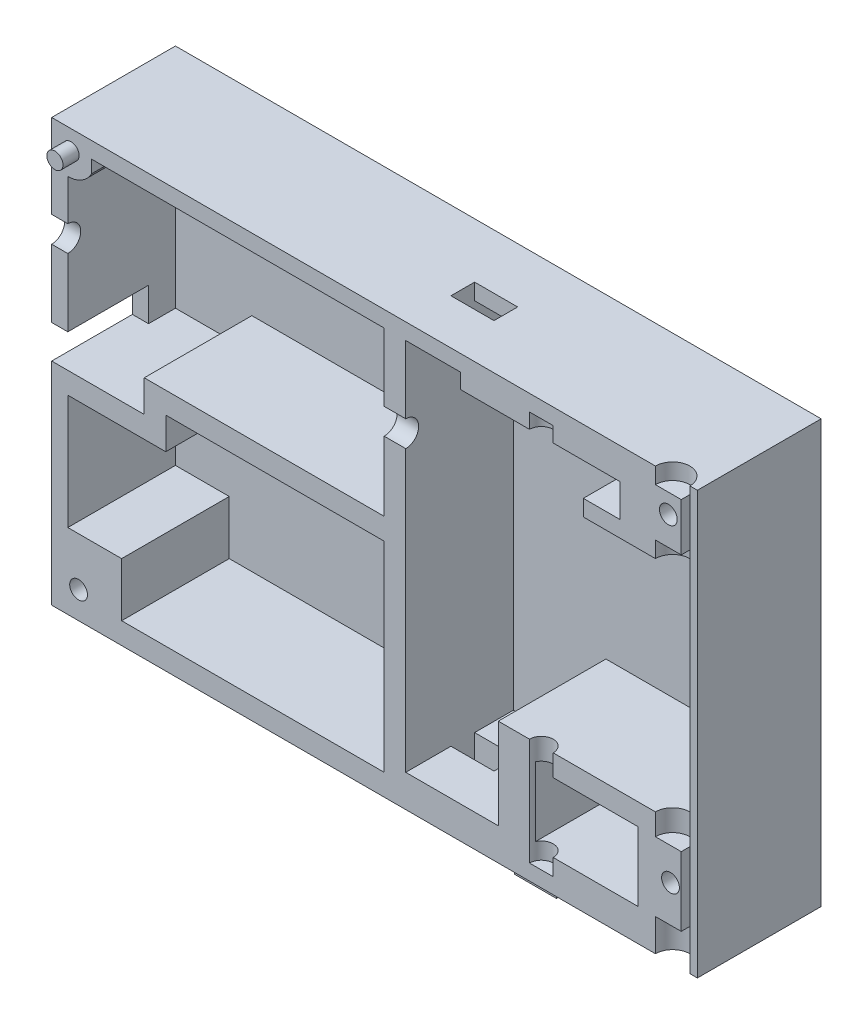
SolidWorks part; units mm, degrees
ref_plane "前视基准面" through (0, 0, 0) normal (0, 0, 1) x (1, 0, 0)
ref_plane "上视基准面" through (0, 0, 0) normal (0, 1, 0) x (1, 0, 0)
ref_plane "右视基准面" through (0, 0, 0) normal (1, 0, 0) x (0, 0, -1)
sketch "草图1" plane through (0, 0, 0) normal (0, 0, 1) x (1, 0, 0)
  line L1 (-30, 26) -> (30, 26)
  line L2 (-30, 26) -> (-30, -26)
  line L3 (-30, -26) -> (30, -26)
  line L4 (30, 26) -> (30, -26)
  line L5 (-30, 26) -> (30, -26) construction
  line L6 (-30, -26) -> (30, 26) construction
  point P0 (0, 0)
  dimension "D1" = 52
  dimension "D2" = 60
extrude "凸台-拉伸1" add sketch "草图1" along normal blind 11.5
shell "抽壳1" thickness 1.5
sketch "草图2" plane through (0, 0, 1.5) normal (0, 0, 1) x (1, 0, 0)
  line L0 (-21.4, 9.35) -> (0.9, 9.35)
  line L1 (-28.5, 24.5) -> (-28.5, -24.5) construction
  line L9 (28.5, -10.25) -> (14.5, -10.25)
  line L14 (0.9, -11.25) -> (0.9, 7.35)
  line L15 (0.9, 7.35) -> (-19.4, 7.35)
  line L17 (0.9, 24.5) -> (0.9, 9.35)
  line L18 (28.5, 24.5) -> (-28.5, 24.5) construction
  line L20 (0.9, 24.5) -> (2.9, 24.5)
  line L21 (8, 24.5) -> (8, 23.1)
  line L22 (8, 23.1) -> (23, 23.1)
  line L23 (23, 23.1) -> (23, 24.5)
  line L24 (23, 24.5) -> (8, 24.5)
  line L28 (2.9, 24.5) -> (2.9, -10.25)
  line L29 (0.8, 14) -> (0.8, 20) construction
  line L30 (-1.2, 9.5) -> (-21.7, 9.5) construction
  line L31 (-21.4, 9.35) -> (-21.4, 6.4)
  line L32 (-21.4, 6.4) -> (-28.5, 6.4)
  line L34 (-28.5, 4.4) -> (-19.4, 4.4)
  line L35 (-19.4, 4.4) -> (-19.4, 7.35)
  line L36 (-21.7, 6.5) -> (-27.2, 6.5) construction
  line L37 (-21.7, 6.5) -> (-21.7, 9.5) construction
  line L38 (15.5, 24.5) -> (15.5, 13.1928) construction
  line L39 (16.5, 24.5) -> (14.5, 24.5) construction
  line L41 (28.5, -13.25) -> (-4.1, -13.25)
  line L48 (19.4, 18.55) -> (28.5, 18.55)
  line L55 (11.5, -10.25) -> (2.9, -10.25)
  line L60 (-28.5, 4.4) -> (-28.5, 6.4)
  line L62 (28.5, -24.5) -> (28.5, 24.5) construction
  line L63 (28.5, 18.55) -> (28.5, 20.05)
  line L64 (28.5, 20.05) -> (19.4, 20.05)
  line L67 (19.4, 20.05) -> (19.4, 18.55)
  line L68 (28.5, -10.25) -> (28.5, -13.25)
  line L69 (11.5, -1.83) -> (28.5, -1.83)
  line L70 (28.5, -1.83) -> (28.5, -3.83)
  line L71 (28.5, -3.83) -> (14.5, -3.83)
  line L73 (0.9, -11.25) -> (-28.5, -11.25)
  line L74 (19.3656, -1.73) -> (20.5824, -1.73) construction
  line L75 (-28.5, -11.25) -> (-28.5, -13.25)
  line L76 (-28.5, -13.25) -> (-4.1, -13.25)
  line L77 (14.5, -3.83) -> (14.5, -10.25)
  line L79 (11.5, -10.25) -> (11.5, -1.83)
  dimension "D3" = 3
  dimension "D4" = 34.75
  dimension "D5" = 1.5
  dimension "D6" = 2
  dimension "D7" = 9.1
  dimension "D8" = 2
  dimension "D9" = 0.15
  dimension "D10" = 2
  dimension "D11" = 0.1
  dimension "D12" = 2
  dimension "D13" = 4.45
  dimension "D14" = 0.1
  dimension "D15" = 0.3
  dimension "D16" = 1.4
  dimension "D17" = 15
  dimension "D18" = 2
  dimension "D19" = 0.1
  dimension "D20" = 17
  dimension "D21" = 2
  dimension "D22" = 3
extrude "凸台-拉伸2" add sketch "草图2" along normal up to surface (10 mm away) up to face at (0, 0, 11.5)
sketch "草图3" plane through (0, -26, 0) normal (0, -1, 0) x (1, 0, 0)
  line L0 (2.9, 7.3) -> (6.9, 7.3)
  line L2 (6.9, 7.3) -> (6.9, 5.1)
  line L3 (6.9, 5.1) -> (2.9, 5.1)
  line L4 (2.9, 5.1) -> (2.9, 7.3)
  line L6 (2.9, 11.5) -> (2.9, 1.5) construction
  line L7 (6.8, 5.2) -> (3, 5.2) construction
  line L8 (6.8, 7.2) -> (3, 7.2) construction
  dimension "D1" = 4
  dimension "D2" = 0.1
  dimension "D3" = 0.1
extrude "变速杆卡位切除-拉伸1" cut sketch "草图3" against normal up to surface (52 mm away) up to face at (0, 26, 5.75)
sketch "草图4" plane through (0, -26, 0) normal (0, -1, 0) x (1, 0, 0)
  circle A0 centre (27.7, 11.5) radius 1.6
  circle A1 centre (27.7, 11.5) radius 1.5 construction
  dimension "D1" = 0.1
extrude "3MM孔切除-拉伸2" cut sketch "草图4" against normal through all
sketch "草图6" plane through (0, 26, 0) normal (0, 1, 0) x (1, 0, 0)
  circle A0 centre (15.5, -11.5) radius 1.1
  circle A1 centre (15.5, -11.5) radius 1 construction
  dimension "D1" = 0.1
extrude "2mm孔切除-拉伸4" cut sketch "草图6" against normal up to surface (36.3 mm away) from surface at -1.5
sketch "草图8" plane through (-30, 0, 0) normal (-1, 0, 0) x (0, 0, 1)
  line L0 (15.5, 9.5) -> (7.5, 9.5) construction
  line L1 (11.5, 9.5) -> (4, 9.5)
  line L2 (11.5, 9.5) -> (11.5, 6.4)
  line L3 (11.5, 6.4) -> (4, 6.4)
  line L4 (4, 9.5) -> (4, 6.4)
  line L5 (0, 26) -> (0, -26) construction
  line L6 (11.5, 6.4) -> (1.5, 6.4) construction
  dimension "D1" = 4
extrude "电机线切除-拉伸5" cut sketch "草图8" against normal up to next
sketch "草图9" plane through (0, 0, 1.5) normal (0, 0, 1) x (1, 0, 0)
  line L0 (-28.5, 4.4) -> (-28.5, -11.25) construction
  line L1 (-28.5, -6.25) -> (-23.5, -6.25)
  line L3 (28.5, 20.05) -> (28.5, 24.5) construction
  line L4 (28.5, 24.5) -> (22.8, 24.5)
  line L5 (28.5, 20.05) -> (28.5, 24.5)
  line L6 (22.8, 24.5) -> (22.8, 20.05)
  line L8 (28.5, 20.05) -> (19.4, 20.05) construction
  line L9 (28.5, 20.05) -> (22.8, 20.05)
  line L11 (-28.5, -6.25) -> (-28.5, -11.25)
  line L13 (-28.5, 24.5) -> (-28.5, 9.5) construction
  line L16 (-28.5, 24.5) -> (-28.5, 22)
  line L23 (-28.5, 24.5) -> (-26.3, 24.5)
  line L24 (24.5, -3.83) -> (28.5, -3.83)
  line L25 (24.5, -3.83) -> (24.5, -10.25)
  line L26 (24.5, -10.25) -> (28.5, -10.25)
  line L27 (28.5, -3.83) -> (28.5, -10.25)
  line L28 (-28.5, -11.25) -> (-23.5, -11.25)
  line L30 (-23.5, -11.25) -> (-23.5, -6.25)
  line L33 (-26.3, 24.5) -> (-26.3, 23.3126)
  line L34 (-26.2, 24.5) -> (-26.2, 9.5) construction
  line L35 (16.6, -3.83) -> (26.1, -3.83) construction
  line L37 (16.6, -10.25) -> (26.1, -10.25) construction
  line L38 (28.5, -10.25) -> (28.5, -3.83) construction
  line L41 (0.9, -11.25) -> (-28.5, -11.25) construction
  circle A0 centre (27.3, 22.7) radius 0.825
  circle A3 centre (27.5, -6.83) radius 0.825
  arc A4 (-26.3, 23.3126) -> (-28.5, 22) centre (-28.5, 24.5) cw
  point P7 (22.8, 22.275)
  dimension "D1" = 1.65
  dimension "D9" = 1.65
  dimension "D12" = 3
  dimension "D15" = 2.5
  dimension "D11" = 1
  dimension "D2" = 1.8
  dimension "D3" = 1.2
  dimension "D5" = 5
  dimension "D6" = 5
  dimension "D10" = 4
  dimension "D17" = 0.1
  dimension "D18" = 4.5
extrude "螺柱支撑凸台-拉伸4" add sketch "草图9" along normal up to surface (10 mm away) up to face at (22.75, 19.3, 11.5)
sketch "草图10" plane through (0, 0, 11.5) normal (0, 0, 1) x (1, 0, 0)
  line L0 (-30, 26) -> (-30, 9.5) construction
  line L3 (26.1, 26) -> (-30, 26) construction
  circle A0 centre (-28.2, 24.2) radius 0.75
  dimension "D1" = 1.5
  dimension "D3" = 1.8
  dimension "D4" = 1.8
extrude "上下楔凸台-拉伸5" add sketch "草图10" along normal blind 1.5
sketch "草图11" plane through (0, 0, 1.5) normal (0, 0, 1) x (1, 0, 0)
  line L0 (16.6, -10.25) -> (24.5, -10.25) construction
  line L1 (7, -15.4) -> (10.9, -15.4)
  line L2 (7, -15.4) -> (7, -19.4)
  line L3 (7, -19.4) -> (10.9, -19.4)
  line L4 (10.9, -15.4) -> (10.9, -19.4)
  line L8 (6.8, 30.7759) -> (6.8, -31.5741) construction
  line L9 (11.1, -7.1991) -> (11.1, 5.8009) construction
  dimension "D1" = 0.2
  dimension "D2" = 0.2
  dimension "D3" = 9.15
  dimension "D4" = 4
extrude "变速卡位凸台-拉伸6" add sketch "草图11" along normal blind 4
sketch "草图13" plane through (0, 0, 11.5) normal (0, 0, 1) x (1, 0, 0)
  line L0 (-28.5, -13.25) -> (26.1, -13.25) construction
  line L1 (-30, 6.4) -> (-30, -26) construction
  circle A1 centre (-27.5, -10.75) radius 0.825
  circle A4 centre (27.3, 22.7) radius 0.825 construction
  circle A5 centre (27.3, 22.7) radius 0.825
  circle A6 centre (27.5, -6.83) radius 0.825 construction
  circle A7 centre (27.5, -6.83) radius 0.825
  dimension "D1" = 2.5
  dimension "D2" = 2.5
extrude "螺孔切除-拉伸1" cut sketch "草图13" against normal up to next
sketch "草图14" plane through (0, 0, 1.5) normal (0, 0, 1) x (1, 0, 0)
  line L0 (-30, 6.4) -> (-30, -26) construction
  line L1 (-30, -13.25) -> (30, -13.25)
  line L2 (-30, -13.25) -> (-30, -26)
  line L3 (-30, -26) -> (30, -26)
  line L4 (30, -13.25) -> (30, -26)
  line L5 (-28.5, -13.25) -> (26.1, -13.25) construction
extrude "切除-拉伸2" cut sketch "草图14" along normal up to next and the other way up to next
sketch "草图15" plane through (0, 0, 11.5) normal (0, 0, 1) x (1, 0, 0)
  circle A0 centre (-28.2, 24.2) radius 0.825
  dimension "D1" = 1.65
extrude "切除-拉伸3" cut sketch "草图15" along normal blind 5 from surface at -11.5 starting at face at (-26.675, -10.75, 0)
sketch "草图16" plane through (-30, 0, 0) normal (-1, 0, 0) x (0, 0, 1)
  circle A0 centre (11.5, 17) radius 1 construction
  circle A1 centre (11.5, 17) radius 1 construction
  circle A2 centre (11.5, 17) radius 1.2
  dimension "D1" = 0.2
extrude "切除-拉伸4" cut sketch "草图16" against normal blind 40
